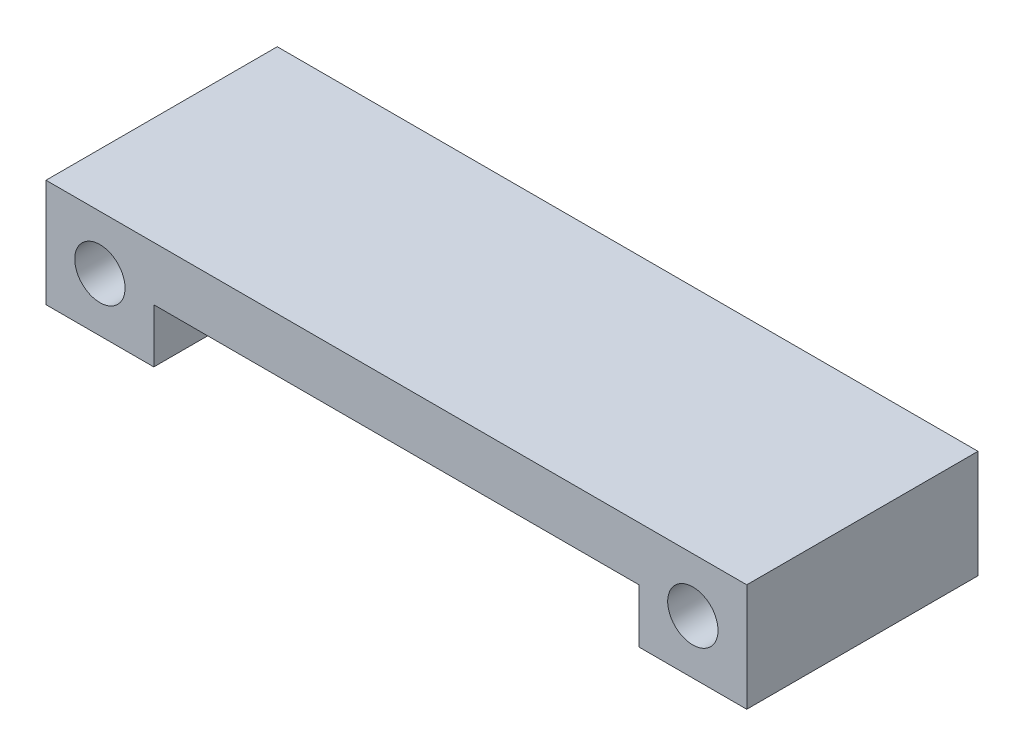
SolidWorks part; units mm, degrees
ref_plane "Front Plane" through (0, 0, 0) normal (0, 0, 1) x (1, 0, 0)
ref_plane "Top Plane" through (0, 0, 0) normal (0, 1, 0) x (1, 0, 0)
ref_plane "Right Plane" through (0, 0, 0) normal (1, 0, 0) x (0, 0, -1)
sketch "Sketch1" plane through (0, 0, 0) normal (0, 0, 1) x (1, 0, 0)
  line L0 (0, 0) -> (0, -16252.7255) construction
  line L1 (-13.5, 0) -> (13.5, 0)
  line L2 (13.5, 0) -> (13.5, -3)
  line L3 (13.5, -3) -> (19.5, -3)
  line L4 (19.5, -3) -> (19.5, 3)
  line L5 (19.5, 3) -> (-19.5, 3)
  line L6 (13.5, -3) -> (19.5, 3) construction
  line L7 (-13.5, -3) -> (-19.5, 3) construction
  line L8 (-19.5, -3) -> (-19.5, 3)
  line L9 (-13.5, -3) -> (-19.5, -3)
  line L10 (-13.5, 0) -> (-13.5, -3)
  circle A0 centre (16.5, 0) radius 1.4
  circle A1 centre (-16.5, 0) radius 1.4
  point P15 (0, 3)
  point P17 (0, 0)
  dimension "D2" = 2.8
  dimension "D1" = 39
  dimension "D3" = 3
  dimension "D4" = 3
  dimension "D5" = 3
extrude "Boss-Extrude1" add sketch "Sketch1" along normal blind 12.87 contours L10 L1 L2 L3 L4 L5 L8 L9 A0 A1
